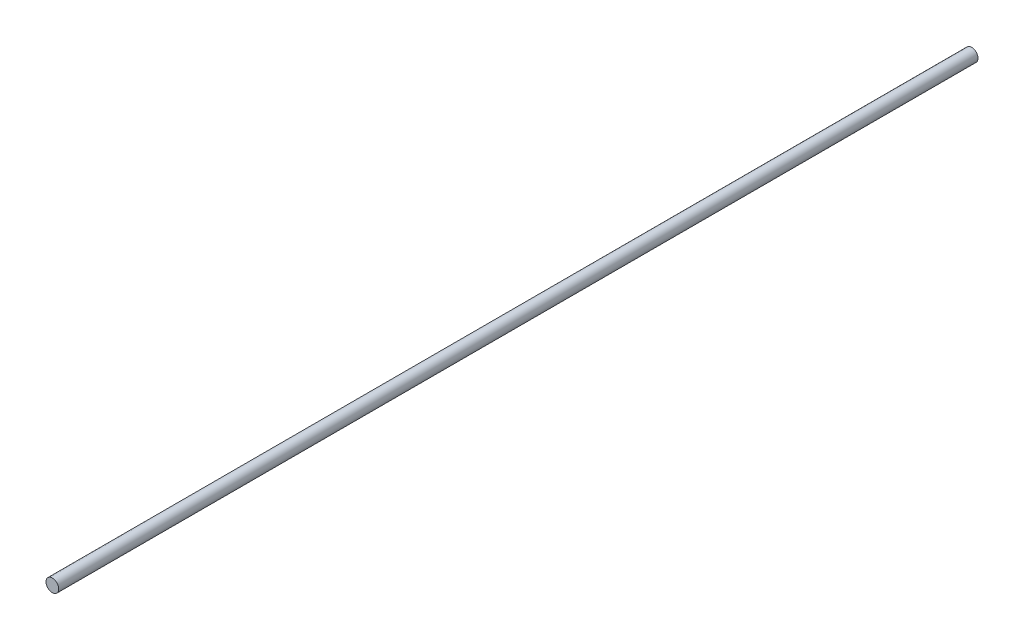
SolidWorks part; units mm, degrees
ref_plane "Plan de face" through (0, 0, 0) normal (0, 0, 1) x (1, 0, 0)
ref_plane "Plan de dessus" through (0, 0, 0) normal (0, 1, 0) x (1, 0, 0)
ref_plane "Plan de droite" through (0, 0, 0) normal (1, 0, 0) x (0, 0, -1)
sketch "Esquisse1" plane through (0, 0, 0) normal (0, 0, 1) x (1, 0, 0)
  circle A0 centre (0, 0) radius 2.105
  dimension "D1" = 4.21
extrude "Boss.-Extru.1" add sketch "Esquisse1" along normal blind 304.5
